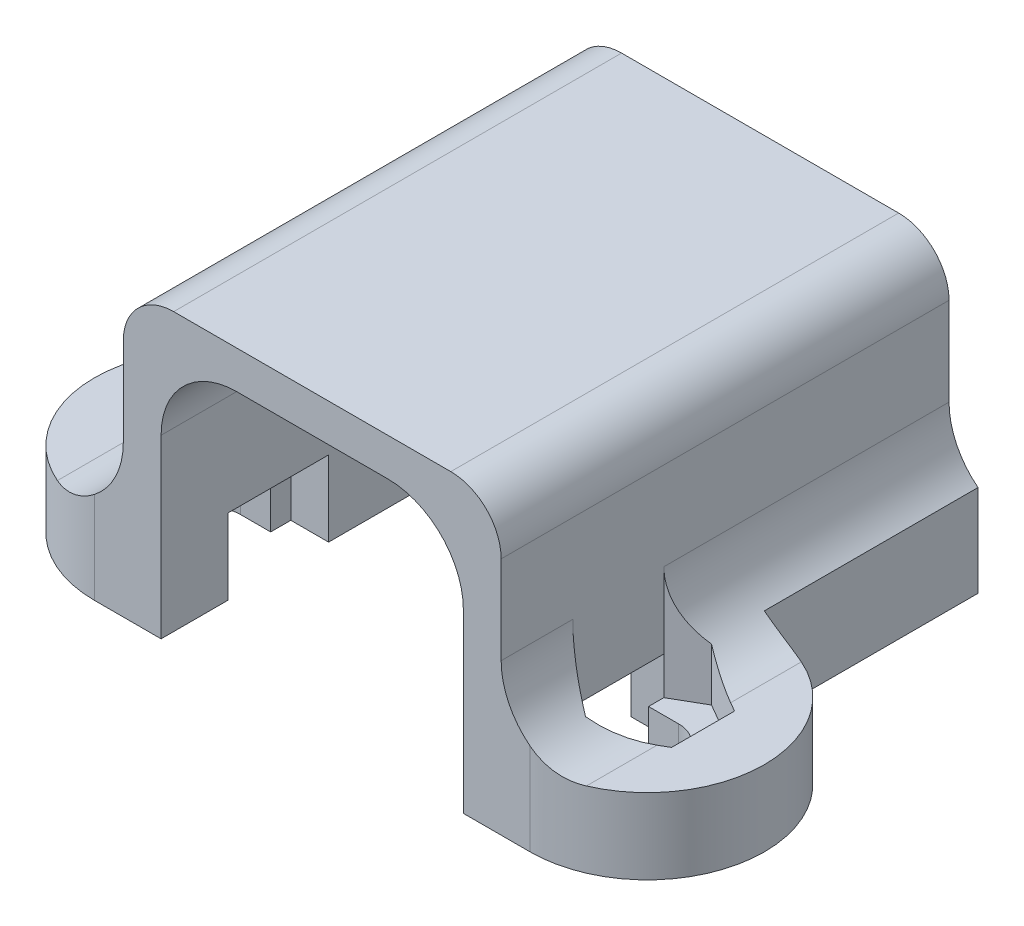
SolidWorks part; units mm, degrees
material "ABS"
ref_plane "Front Plane" through (0, 0, 0) normal (0, 0, 1) x (1, 0, 0)
ref_plane "Top Plane" through (0, 0, 0) normal (0, 1, 0) x (1, 0, 0)
ref_plane "Right Plane" through (0, 0, 0) normal (1, 0, 0) x (0, 0, -1)
sketch "Sketch1" plane through (0, 0, 0) normal (0, 0, 1) x (1, 0, 0)
  line L0 (0, 0) -> (26.6, 0)
  line L1 (26.6, 0) -> (26.6, 3)
  line L2 (26.6, 3) -> (20.8, 3)
  line L3 (20.8, 3) -> (20.8, 11.5)
  line L4 (20.8, 11.5) -> (5.8, 11.5)
  line L5 (5.8, 11.5) -> (5.8, 3)
  line L6 (5.8, 3) -> (0, 3)
  line L7 (0, 3) -> (0, 0)
  line L8 (7.3, 0) -> (7.3, 10)
  line L9 (13.3, 0) -> (13.3, 10)
  line L10 (19.3, 10) -> (19.3, 0)
  line L11 (13.3, 10) -> (7.3, 10)
  line L12 (13.3, 10) -> (19.3, 10)
  dimension "D1" = 26.6
  dimension "D2" = 3
  dimension "D3" = 12
  dimension "D4" = 11.5
  dimension "D5" = 15
  dimension "D6" = 1.5
extrude "Boss-Extrude1" add sketch "Sketch1" against normal blind 17.78 contours L11 L12 L10 L0 L1 L2 L3 L4 L5 L6 L7 L8
fillet "Fillet1" radius 2 2 edges at (20.8, 11.5, -8.89) (5.8, 11.5, -8.89)
fillet "Fillet2" radius 3 2 edges at (20.8, 3, -8.89) (5.8, 3, -8.89)
sketch "Sketch2" plane through (0, 0, 0) normal (0, 1, 0) x (1, 0, 0)
  line L0 (0, 0) -> (4.65, 0)
  line L1 (4.65, 0) -> (4.65, 9.3)
  line L2 (2.8, 0) -> (5.8, 0) construction
  line L3 (4.65, 9.3) -> (4.65, 17.78)
  line L4 (4.65, 0) -> (13.3, 0)
  line L5 (18.8, 0) -> (7.8, 0) construction
  line L7 (4.65, 17.78) -> (0, 17.78)
  line L8 (0, 17.78) -> (0, 0)
  line L9 (13.3, 0) -> (13.3, 5.538) construction
  line L10 (26.6, 0) -> (21.95, 0)
  line L11 (26.6, 17.78) -> (26.6, 0)
  line L12 (21.95, 17.78) -> (26.6, 17.78)
  line L13 (21.95, 9.3) -> (21.95, 17.78)
  arc A0 (4.65, 0) -> (4.65, 9.3) centre (4.65, 4.65) cw
  arc A1 (21.95, 0) -> (21.95, 9.3) centre (21.95, 4.65) ccw
  dimension "D1" = 4.65
  dimension "D2" = 9.3
extrude "Cut-Extrude5" cut sketch "Sketch2" along normal through all contours L8 A0 L3 L7 | L0 A0 L8 | A1 L11 L12 L13 | A1 L10 L11
sketch "Sketch3" plane through (0, 0, 0) normal (0, -1, 0) x (1, 0, 0)
  line L0 (7.3, -2.65) -> (7.3, 0)
  line L1 (7.3, -17.78) -> (7.3, 0) construction
  line L2 (7.3, -17.78) -> (7.3, 0) construction
  line L3 (7.3, -6.65) -> (5.8, -6.65)
  line L4 (5.8, -6.65) -> (5.8, -5.85)
  line L5 (7.3, -2.65) -> (5.8, -2.65)
  line L6 (5.8, -2.65) -> (5.8, -3.45)
  line L7 (5.8, -3.45) -> (4.6, -3.45)
  line L8 (4.6, -3.45) -> (4.6, -5.85)
  line L9 (4.6, -5.85) -> (5.8, -5.85)
  line L10 (0, 0) -> (7.3, 0)
  line L11 (7.3, 0) -> (13.3, 0)
  line L12 (19.3, 0) -> (7.3, 0) construction
  line L13 (13.3, 0) -> (13.3, -1.2825)
  line L14 (22, -5.85) -> (20.8, -5.85)
  line L15 (20.8, -6.65) -> (20.8, -5.85)
  line L16 (19.3, -6.65) -> (20.8, -6.65)
  line L17 (19.3, -2.65) -> (20.8, -2.65)
  line L18 (20.8, -2.65) -> (20.8, -3.45)
  line L19 (20.8, -3.45) -> (22, -3.45)
  line L20 (19.3, -2.65) -> (19.3, -6.65)
  circle A0 centre (22, -4.65) radius 1.2
  circle A1 centre (4.6, -4.65) radius 1.2
  dimension "D2" = 2.4
  dimension "D1" = 4
  dimension "D3" = 1.5
  dimension "D4" = 4.65
  dimension "D5" = 2.4
extrude "Cut-Extrude6" cut sketch "Sketch3" against normal blind 3
sketch "Sketch4" plane through (0, 3, 0) normal (0, 1, 0) x (1, 0, 0)
  line L0 (4.6, 4.65) -> (4.6, 7.15)
  line L1 (4.6, 7.15) -> (2.4349, 5.9)
  line L2 (2.4349, 5.9) -> (2.4349, 3.4)
  line L3 (2.4349, 3.4) -> (4.6, 2.15)
  line L4 (4.6, 2.15) -> (4.6, 4.65)
  line L5 (4.6, 7.15) -> (5.8, 6.4572)
  line L6 (5.8, 17.78) -> (5.8, 0) construction
  line L7 (5.8, 6.4572) -> (5.8, 2.8428)
  line L8 (5.8, 2.8428) -> (4.6, 2.15)
  line L9 (13.3, 0) -> (13.3, 2.0344)
  line L10 (18.8, 0) -> (7.8, 0) construction
  line L11 (24.1651, 3.4) -> (22, 2.15)
  line L12 (22, 2.15) -> (22, 4.65)
  line L13 (20.8, 2.8428) -> (22, 2.15)
  line L14 (20.8, 6.4572) -> (20.8, 2.8428)
  line L15 (22, 7.15) -> (20.8, 6.4572)
  line L16 (22, 4.65) -> (22, 7.15)
  line L17 (22, 7.15) -> (24.1651, 5.9)
  line L18 (24.1651, 5.9) -> (24.1651, 3.4)
  point P0 (4.6, 4.65)
  line M2 (2.8, 0.3839) -> (2.8, 8.9161)
  dimension "D1" = 2.5
  dimension "D2" = 120
  dimension "D3" = 120
extrude "Cut-Extrude7" cut sketch "Sketch4" against normal blind 1.5 and the other way blind 3 contours L2 L3 L1 M2 | L3 L4 L0 L1 M2 | L8 L7 L5 L0 L4 | L12 L16 L15 L14 L13 | L18 L17 L16 L12 L11
sketch "Sketch5" plane through (0, 0, 0) normal (0, 0, -1) x (-1, 0, 0)
  line L0 (-19.3, 10) -> (-16.3, 7)
  line L1 (-19.3, 10) -> (-7.3, 10) construction
  line L2 (-19.3, 10) -> (-19.3, 0) construction
  line L3 (-16.3, 10) -> (-19.3, 10)
  line L4 (-19.3, 10) -> (-19.3, 7)
  line L5 (-13.3, 10) -> (-13.3, 9.1237)
  line L6 (-7.3, 10) -> (-7.3, 7)
  line L7 (-10.3, 10) -> (-7.3, 10)
  arc A0 (-16.3, 10) -> (-19.3, 7) centre (-16.3, 7) ccw
  arc A1 (-10.3, 10) -> (-7.3, 7) centre (-10.3, 7) cw
  dimension "D1" = 45
  dimension "D2" = 3
extrude "Boss-Extrude2" add sketch "Sketch5" along normal blind 8
